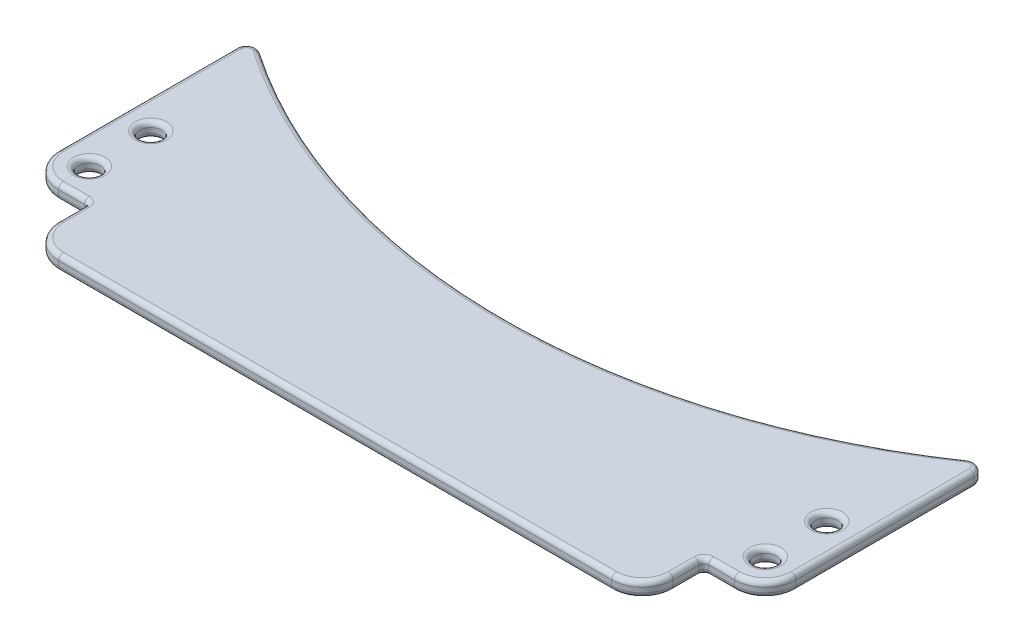
SolidWorks part; units mm, degrees
ref_plane "Front Plane" through (0, 0, 0) normal (0, 0, 1) x (1, 0, 0)
ref_plane "Top Plane" through (0, 0, 0) normal (0, 1, 0) x (1, 0, 0)
ref_plane "Right Plane" through (0, 0, 0) normal (1, 0, 0) x (0, 0, -1)
sketch "Sketch1" plane through (0, 0, 0) normal (0, 1, 0) x (1, 0, 0)
  line L10 (0, 0) -> (0, -80) construction
  line L13 (-63.5, -165) -> (63.5, -165)
  line L14 (-63.5, -165) -> (-63.5, -152.3)
  line L15 (-63.5, -152.3) -> (-76.2, -152.3)
  line L16 (-76.2, -152.3) -> (-76.2, -105.326)
  line L18 (63.5, -165) -> (63.5, -152.3)
  line L20 (76.2, -152.3) -> (76.2, -105.326)
  line L21 (63.5, -152.3) -> (76.2, -152.3)
  circle A0 centre (0, 0) radius 130 construction
  arc A1 (-76.2, -105.326) -> (76.2, -105.326) centre (0, 0) ccw
  circle A8 centre (-69.85, -145.95) radius 2.25
  circle A9 centre (-69.85, -133.25) radius 2.25
  circle A10 centre (69.85, -133.25) radius 2.25
  circle A11 centre (69.85, -145.95) radius 2.25
  point P5 (0, -165)
  point P15 (0, 0)
  point P25 (0, 0)
  point P26 (-76.2, -101.6559)
  point P27 (0, 0)
  point P28 (0, 0)
  dimension "D1" = 260
  dimension "D10" = 6.35
  dimension "D7" = 4.5
  dimension "D2" = 165
  dimension "D3" = 63.5
  dimension "D4" = 12.7
  dimension "D5" = 12.7
  dimension "D8" = 12.7
  dimension "D9" = 6.35
extrude "Boss-Extrude1" add sketch "Sketch1" along normal blind 3
fillet "Fillet5" radius 6.35 4 edges at (-76.2, 1.5, 152.3) (-63.5, 1.5, 165) (63.5, 1.5, 165) (76.2, 1.5, 152.3)
fillet "Fillet6" radius 2 2 edges at (76.2, 1.5, 105.326) (-76.2, 1.5, 105.326)
fillet "Fillet7" radius 1 38 edges at (69.85, 0, 148.2) (-76.2, 0, 127.5606) (-74.3401, 0, 150.4401) (-66.675, 0, 152.3) (-63.5, 0, 155.475) (-61.6401, 0, 163.1401) (0, 0, 165) (61.6401, 0, 163.1401) (63.5, 0, 155.475) (66.675, 0, 152.3) (74.3401, 0, 150.4401) (76.2, 0, 127.5606) (0, 0, 130) (-69.85, 0, 148.2) (-69.85, 0, 135.5) (69.85, 0, 135.5) (69.85, 3, 148.2) (76.2, 3, 127.5606) (74.3401, 3, 150.4401) (66.675, 3, 152.3) (63.5, 3, 155.475) (61.6401, 3, 163.1401) (0, 3, 165) (-61.6401, 3, 163.1401) (-63.5, 3, 155.475) (-66.675, 3, 152.3) (-74.3401, 3, 150.4401) (-76.2, 3, 127.5606) (0, 3, 130) (-69.85, 3, 148.2) (-69.85, 3, 135.5) (69.85, 3, 135.5) (63.5, 1.5, 152.3) (-63.5, 1.5, 152.3) (-75.1358, 0, 107.4037) (75.1358, 0, 107.4037) (-75.1358, 3, 107.4037) (75.1358, 3, 107.4037)
